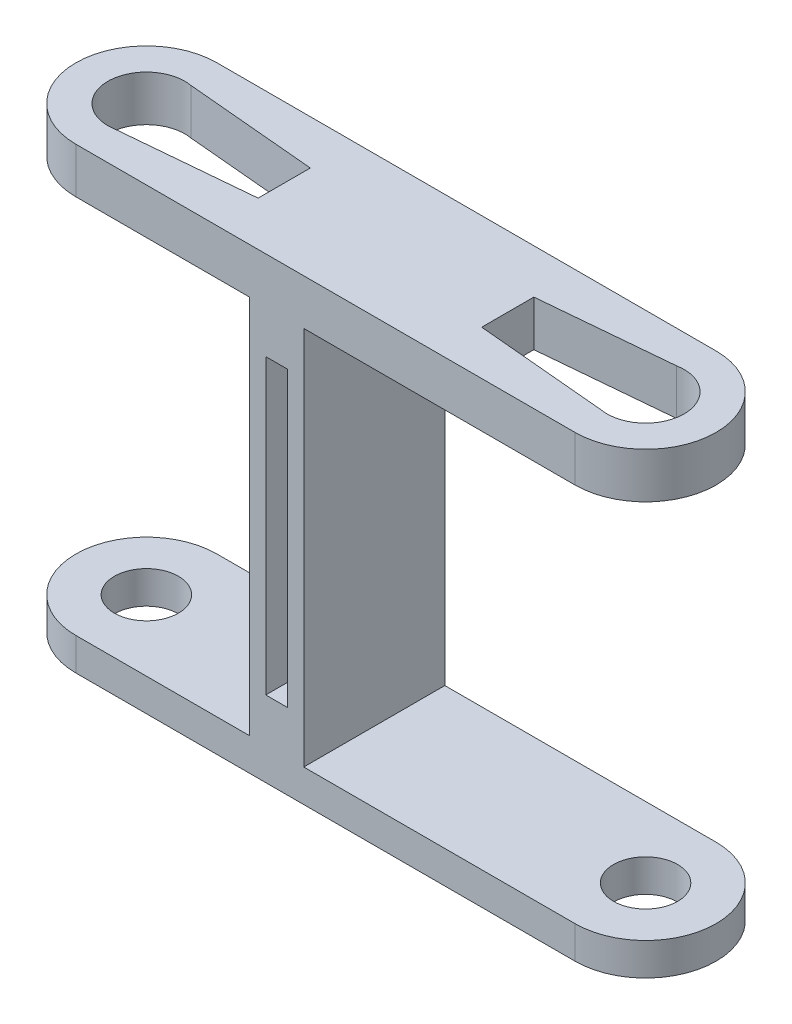
SolidWorks part; units mm, degrees
material "ABS"
ref_plane "Front Plane" through (0, 0, 0) normal (0, 0, 1) x (1, 0, 0)
ref_plane "Top Plane" through (0, 0, 0) normal (0, 1, 0) x (1, 0, 0)
ref_plane "Right Plane" through (0, 0, 0) normal (1, 0, 0) x (0, 0, -1)
sketch "Sketch1" plane through (0, 0, 0) normal (0, 1, 0) x (1, 0, 0)
  circle A0 centre (0, 0) radius 6.5
  circle A1 centre (46, 0) radius 6.5
extrude "Boss-Extrude1" add sketch "Sketch1" along normal mid plane 4.2 from offset 43.6
sketch "Sketch2" plane through (0, 0, 0) normal (0, 1, 0) x (1, 0, 0)
  line L1 (0, -6.5) -> (46, -6.5)
  line L2 (0, -6.5) -> (0, 6.5)
  line L3 (0, 6.5) -> (46, 6.5)
  line L4 (46, -6.5) -> (46, 6.5)
  circle A0 centre (0, 0) radius 6.5 construction
  circle A1 centre (46, 0) radius 6.5 construction
extrude "Boss-Extrude2" add sketch "Sketch2" along normal mid plane 4.2 from offset 43.6
sketch "Sketch3" plane through (0, 0, 0) normal (0, 1, 0) x (1, 0, 0)
  circle A0 centre (0, 0) radius 3.55
  circle A1 centre (46, 0) radius 3.55
extrude "Cut-Extrude1" cut sketch "Sketch3" against normal mid plane 4.2 from offset 43.6
sketch "Sketch4" plane through (0, 0, 0) normal (0, 1, 0) x (1, 0, 0)
  line L0 (0, -3.55) -> (12.7, -2.4033)
  line L1 (12.7, -2.4033) -> (12.7, 2.4033)
  line L2 (12.7, 2.4033) -> (0, 3.55)
  line L3 (0, 3.55) -> (0, -3.55)
  line L4 (46, 3.55) -> (33.3, 2.4033)
  line L5 (33.3, 2.4033) -> (33.3, -2.4033)
  line L6 (33.3, -2.4033) -> (46, -3.55)
  line L7 (46, -3.55) -> (46, 3.55)
  circle A0 centre (0, 0) radius 3.55 construction
  circle A1 centre (46, 0) radius 3.55 construction
extrude "Cut-Extrude2" cut sketch "Sketch4" against normal mid plane 4.2 from offset 43.6
sketch "Sketch5" plane through (0, 0, 0) normal (0, 1, 0) x (1, 0, 0)
  circle A0 centre (0, 0) radius 6.5
  circle A1 centre (46, 0) radius 6.5
extrude "Boss-Extrude3" add sketch "Sketch5" along normal mid plane 3 from offset 5
sketch "Sketch6" plane through (0, 0, 0) normal (0, 1, 0) x (1, 0, 0)
  line L1 (0, -6.5) -> (46, -6.5)
  line L2 (0, -6.5) -> (0, 6.5)
  line L3 (0, 6.5) -> (46, 6.5)
  line L4 (46, -6.5) -> (46, 6.5)
extrude "Boss-Extrude4" add sketch "Sketch6" along normal mid plane 3 from offset 5
sketch "Sketch7" plane through (0, 0, 0) normal (0, 1, 0) x (1, 0, 0)
  circle A0 centre (0, 0) radius 2.95
  circle A1 centre (46, 0) radius 2.95
extrude "Cut-Extrude3" cut sketch "Sketch7" against normal mid plane 3 from offset 5
sketch "Sketch8" plane through (0, 0, 0) normal (1, 0, 0) x (0, 0, -1)
  line L1 (-6.5, 3.5) -> (6.5, 3.5)
  line L2 (-6.5, 3.5) -> (-6.5, 45.7)
  line L3 (-6.5, 45.7) -> (6.5, 45.7)
  line L4 (6.5, 3.5) -> (6.5, 45.7)
extrude "Boss-Extrude5" add sketch "Sketch8" along normal mid plane 5 from offset 18.5
sketch "Sketch9" plane through (0, 0, 0) normal (0, 0, 1) x (1, 0, 0)
  line L1 (17.5, 10.5) -> (19.5, 10.5)
  line L2 (17.5, 10.5) -> (17.5, 37.5)
  line L3 (17.5, 37.5) -> (19.5, 37.5)
  line L4 (19.5, 10.5) -> (19.5, 37.5)
extrude "Cut-Extrude4" cut sketch "Sketch9" against normal mid plane 13.02 from offset 0.01
